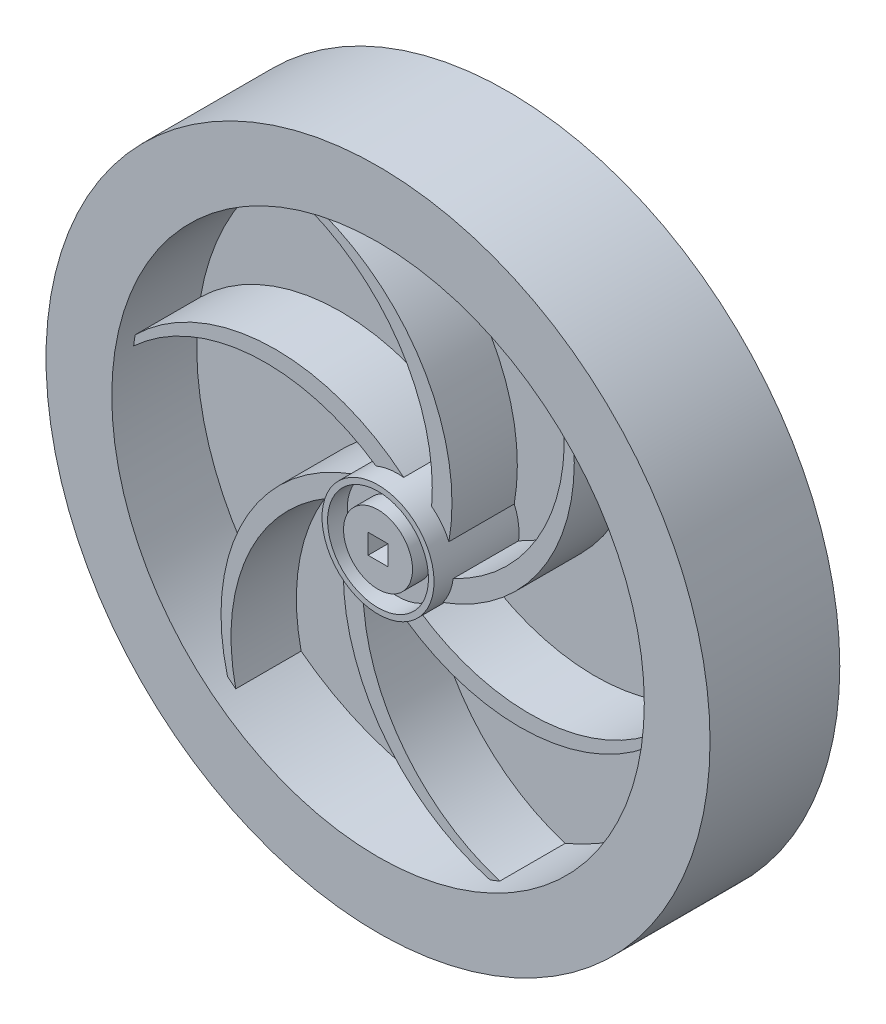
SolidWorks part; units mm, degrees
ref_plane "Front Plane" through (0, 0, 0) normal (0, 0, 1) x (1, 0, 0)
ref_plane "Top Plane" through (0, 0, 0) normal (0, 1, 0) x (1, 0, 0)
ref_plane "Right Plane" through (0, 0, 0) normal (1, 0, 0) x (0, 0, -1)
sketch "Sketch1" plane through (0, 0, 0) normal (0, 0, 1) x (1, 0, 0)
  line L0 (-1.525, 1.525) -> (1.525, -1.525) construction
  line L1 (-1.525, -1.525) -> (1.525, -1.525)
  line L2 (-1.525, -1.525) -> (-1.525, 1.525)
  line L3 (-1.525, 1.525) -> (1.525, 1.525)
  line L4 (1.525, -1.525) -> (1.525, 1.525)
  line L5 (1.525, 1.525) -> (-1.525, -1.525) construction
  circle A0 centre (0, 0) radius 50.8
  circle A1 centre (0, 0) radius 8.57
  circle A2 centre (0, 0) radius 5.275
  circle A3 centre (0, 0) radius 7.72
  point P4 (0, 0)
  dimension "D3" = 101.6
  dimension "D4" = 17.14
  dimension "D5" = 10.55
  dimension "D6" = 0.85
  dimension "D1" = 3.05
  dimension "D2" = 3.05
extrude "Boss-Extrude1" add sketch "Sketch1" along normal blind 19.85 contours A2 L4 L1 L2 L3 | A3 A2 | A1 A3 | A0 A1
sketch "Sketch2" plane through (0, 0, 19.85) normal (0, 0, 1) x (1, 0, 0)
  circle A0 centre (0, 0) radius 7.72
  circle A1 centre (0, 0) radius 5.275
  circle A2 centre (0, 0) radius 8.57
  dimension "D1" = 15.44
  dimension "D2" = 10.55
  dimension "D3" = 17.14
extrude "Cut-Extrude1" cut sketch "Sketch2" against normal blind 3 contours A0 A1
sketch "Sketch3" plane through (0, 0, 19.85) normal (0, 0, 1) x (1, 0, 0)
  line L0 (1.525, 1.525) -> (-1.525, -1.525) construction
  circle A0 centre (0, 0) radius 40.74
  circle A1 centre (0, 0) radius 8.57
  dimension "D1" = 81.48
  dimension "D2" = 17.14
extrude "Cut-Extrude2" cut sketch "Sketch3" against normal blind 3
sketch "Sketch4" plane through (0, 0, 0) normal (0, 0, -1) x (-1, 0, 0)
  circle A0 centre (0, 0) radius 45.3378
  circle A1 centre (0, 0) radius 8.57
  circle A2 centre (0, 0) radius 7.72
  circle A3 centre (0, 0) radius 5.275
  dimension "D1" = 90.6757
  dimension "D2" = 17.14
  dimension "D3" = 15.44
  dimension "D4" = 10.55
extrude "Cut-Extrude3" cut sketch "Sketch4" against normal blind 3 contours A0 A1 | A2 A3
sketch "Sketch5" plane through (0, 0, 16.85) normal (0, 0, 1) x (1, 0, 0)
  line L0 (0, 40.74) -> (0, -40.74) construction
  line L1 (0, 5.275) -> (-40.3971, 5.275) construction
  circle A0 centre (0, 0) radius 40.74 construction
  circle A1 centre (0, 0) radius 40.74 construction
  arc A2 (0, 5.275) -> (-40.3971, 5.275) centre (-20.1985, -16.5966) ccw
  circle A3 centre (0, 0) radius 5.275 construction
  arc A4 (-40.1557, 6.875) -> (2.18, 7.4058) centre (-18.7126, -14.8147) cw
  circle A5 centre (0, 0) radius 7.72 construction
  arc A6 (-14.1239, 38.2134) -> (7.5036, 1.815) centre (-22.1862, 8.7982) cw
  arc A7 (4.5683, 2.6375) -> (-15.6302, 37.6224) centre (-24.4723, 9.1942) ccw
  arc A8 (26.0318, 31.3384) -> (5.3236, -5.5908) centre (-3.4736, 23.6129) cw
  arc A9 (4.5683, -2.6375) -> (24.7668, 32.3474) centre (-4.2738, 25.7907) ccw
  arc A10 (40.1557, -6.875) -> (-2.18, -7.4058) centre (18.7126, 14.8147) cw
  arc A11 (0, -5.275) -> (40.3971, -5.275) centre (20.1985, 16.5966) ccw
  arc A12 (14.1239, -38.2134) -> (-7.5036, -1.815) centre (22.1862, -8.7982) cw
  arc A13 (-4.5683, -2.6375) -> (15.6302, -37.6224) centre (24.4723, -9.1942) ccw
  arc A14 (-26.0318, -31.3384) -> (-5.3236, 5.5908) centre (3.4736, -23.6129) cw
  arc A15 (-4.5683, 2.6375) -> (-24.7668, -32.3474) centre (4.2738, -25.7907) ccw
  circle A16 centre (0, 0) radius 8.57
  circle A17 centre (0, 0) radius 7.72
  circle A18 centre (0, 0) radius 5.275
  point P9 (-20.1985, 13.175)
  point P54 (0, 0)
  circle M3 centre (0, 0) radius 8.57
  circle M4 centre (0, 0) radius 40.74
  dimension "D1" = 7.9
  dimension "D3" = 30.5
  dimension "D6" = 17.14
  dimension "D7" = 15.44
  dimension "D8" = 10.55
  dimension "D2" = 2.18
  dimension "D4" = 1.6
  dimension "D5" = 6
extrude "Cut-Extrude4" cut sketch "Sketch5" against normal blind 10 contours A7 A4 M3 M4 | A9 A6 M3 M4 | A11 A8 M3 M4 | A13 A10 M3 M4 | A15 A12 M3 M4 | A14 A2 M4 M3
